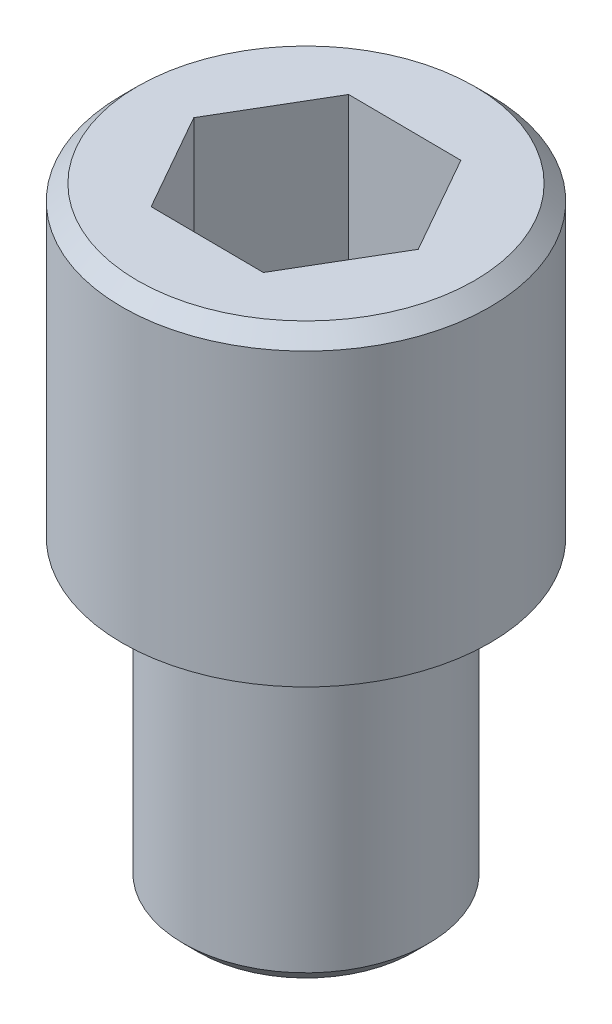
SolidWorks part; units mm, degrees
ref_plane "Přední rovina" through (0, 0, 0) normal (0, 0, 1) x (1, 0, 0)
ref_plane "Horní rovina" through (0, 0, 0) normal (0, 1, 0) x (1, 0, 0)
ref_plane "Pravá rovina" through (0, 0, 0) normal (1, 0, 0) x (0, 0, -1)
sketch "Skica1" plane through (0, 0, 0) normal (0, 1, 0) x (1, 0, 0)
  circle A0 centre (0, 0) radius 2
  dimension "D1" = 4
extrude "Přidat vysunutím1" add sketch "Skica1" along normal blind 5
sketch "Skica2" plane through (0, 5, 0) normal (0, 1, 0) x (1, 0, 0)
  circle A0 centre (0, 0) radius 3
extrude "Přidat vysunutím2" add sketch "Skica2" along normal blind 5
sketch "Skica3" plane through (0, 10, 0) normal (0, 1, 0) x (1, 0, 0)
  line L1 (-0.9365, -1.5926) -> (0.9109, -1.6073)
  line L2 (0.9109, -1.6073) -> (1.8475, -0.0148)
  line L3 (1.8475, -0.0148) -> (0.9365, 1.5926)
  line L4 (0.9365, 1.5926) -> (-0.9109, 1.6073)
  line L5 (-0.9109, 1.6073) -> (-1.8475, 0.0148)
  line L6 (-1.8475, 0.0148) -> (-0.9365, -1.5926)
  circle A0 centre (0, 0) radius 1.6 construction
  dimension "D1" = 3.2
extrude "Odebrat vysunutím1" cut sketch "Skica3" against normal blind 3
chamfer "Zkosení1" distance 0.25 angle 45 2 edges at (0, 0, 2) (0, 10, 3)
